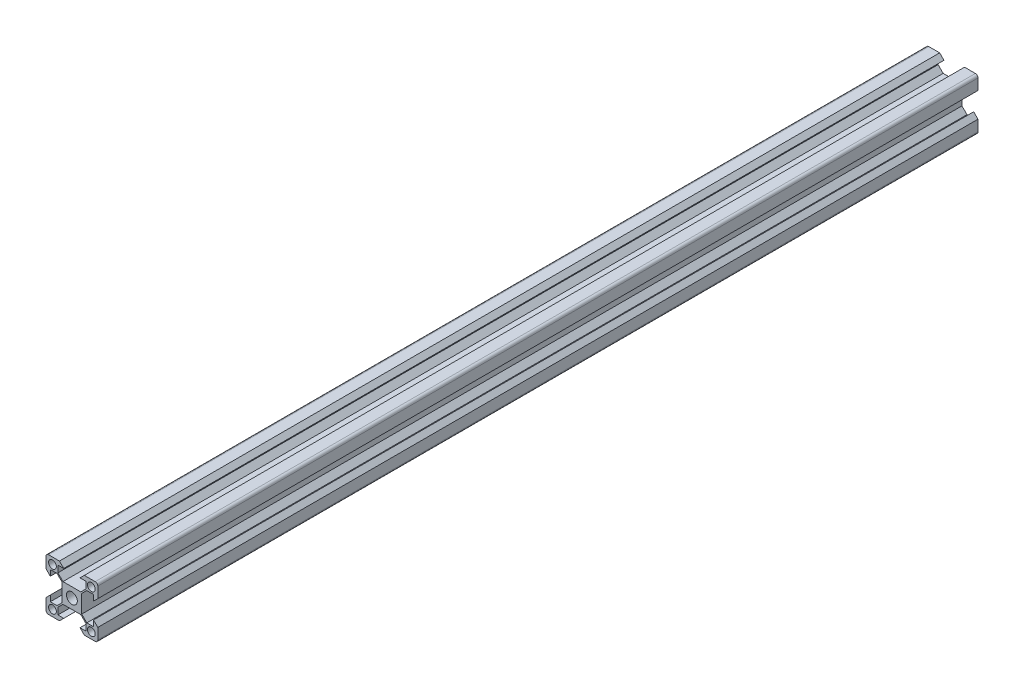
SolidWorks part; units mm, degrees
material "铝管"
ref_plane "前视基准面" through (0, 0, 0) normal (0, 0, 1) x (1, 0, 0)
ref_plane "上视基准面" through (0, 0, 0) normal (0, 1, 0) x (1, 0, 0)
ref_plane "右视基准面" through (0, 0, 0) normal (1, 0, 0) x (0, 0, -1)
sketch "草图1" plane through (0, 0, 0) normal (0, 0, 1) x (1, 0, 0)
  line L0 (0, 0) -> (-40.5659, 40.5659) construction
  line L1 (0, 0) -> (0, 75.5033) construction
  line L2 (-10, 10) -> (-10, 4.8)
  line L3 (-10, 4.8) -> (-8.34, 3.14)
  line L4 (-8.34, 3.14) -> (-8.34, 5.4)
  line L5 (-5.7536, 5.4) -> (-3.8, 3.4464)
  line L6 (-3.8, 3.4464) -> (-3.8, -3.4464)
  line L7 (-3.8, 0) -> (15.6715, 0) construction
  line L8 (-5.4, 8.34) -> (-5.4, 5.7536)
  line L9 (-3.4464, 3.8) -> (3.4464, 3.8)
  line L10 (-5.4, 5.7536) -> (-3.4464, 3.8)
  line L11 (-3.14, 8.34) -> (-5.4, 8.34)
  line L12 (-8.34, 5.4) -> (-5.7536, 5.4)
  line L13 (-4.8, 10) -> (-3.14, 8.34)
  line L14 (-10, 10) -> (-4.8, 10)
  line L15 (-10, -10) -> (-4.8, -10)
  line L16 (-4.8, -10) -> (-3.14, -8.34)
  line L17 (-8.34, -5.4) -> (-5.7536, -5.4)
  line L18 (-3.14, -8.34) -> (-5.4, -8.34)
  line L19 (-5.4, -5.7536) -> (-3.4464, -3.8)
  line L20 (-3.4464, -3.8) -> (3.4464, -3.8)
  line L21 (-5.4, -8.34) -> (-5.4, -5.7536)
  line L22 (-5.7536, -5.4) -> (-3.8, -3.4464)
  line L23 (-8.34, -3.14) -> (-8.34, -5.4)
  line L24 (-10, -4.8) -> (-8.34, -3.14)
  line L25 (-10, -10) -> (-10, -4.8)
  line L26 (10, -10) -> (10, -4.8)
  line L27 (10, -4.8) -> (8.34, -3.14)
  line L28 (8.34, -3.14) -> (8.34, -5.4)
  line L29 (5.7536, -5.4) -> (3.8, -3.4464)
  line L30 (5.4, -8.34) -> (5.4, -5.7536)
  line L31 (5.4, -5.7536) -> (3.4464, -3.8)
  line L32 (3.14, -8.34) -> (5.4, -8.34)
  line L33 (8.34, -5.4) -> (5.7536, -5.4)
  line L34 (4.8, -10) -> (3.14, -8.34)
  line L35 (10, -10) -> (4.8, -10)
  line L36 (10, 10) -> (4.8, 10)
  line L37 (4.8, 10) -> (3.14, 8.34)
  line L38 (8.34, 5.4) -> (5.7536, 5.4)
  line L39 (3.14, 8.34) -> (5.4, 8.34)
  line L40 (5.4, 5.7536) -> (3.4464, 3.8)
  line L41 (5.4, 8.34) -> (5.4, 5.7536)
  line L42 (3.8, 3.4464) -> (3.8, -3.4464)
  line L43 (5.7536, 5.4) -> (3.8, 3.4464)
  line L44 (8.34, 3.14) -> (8.34, 5.4)
  line L45 (10, 4.8) -> (8.34, 3.14)
  line L46 (10, 10) -> (10, 4.8)
  circle A0 centre (-7.5, 7.5) radius 1.5
  circle A1 centre (0, 0) radius 2.1
  circle A2 centre (-7.5, -7.5) radius 1.5
  circle A3 centre (7.5, -7.5) radius 1.5
  circle A4 centre (7.5, 7.5) radius 1.5
  point P54 (0, -3.8)
  point P64 (0, 3.8)
  dimension "D6" = 3
  dimension "D7" = 7.5
  dimension "D9" = 4.2
  dimension "D1" = 45
  dimension "D2" = 4.8
  dimension "D3" = 3.8
  dimension "D4" = 10
  dimension "D5" = 5.4
  dimension "D8" = 3.14
  dimension "D10" = 10
  dimension "D11" = 0.5
extrude "凸台-拉伸1" add sketch "草图1" along normal mid plane 340
fillet "圆角1" radius 1 4 edges at (-10, -10, 0) (10, -10, 0) (-10, 10, 0) (10, 10, 0)
